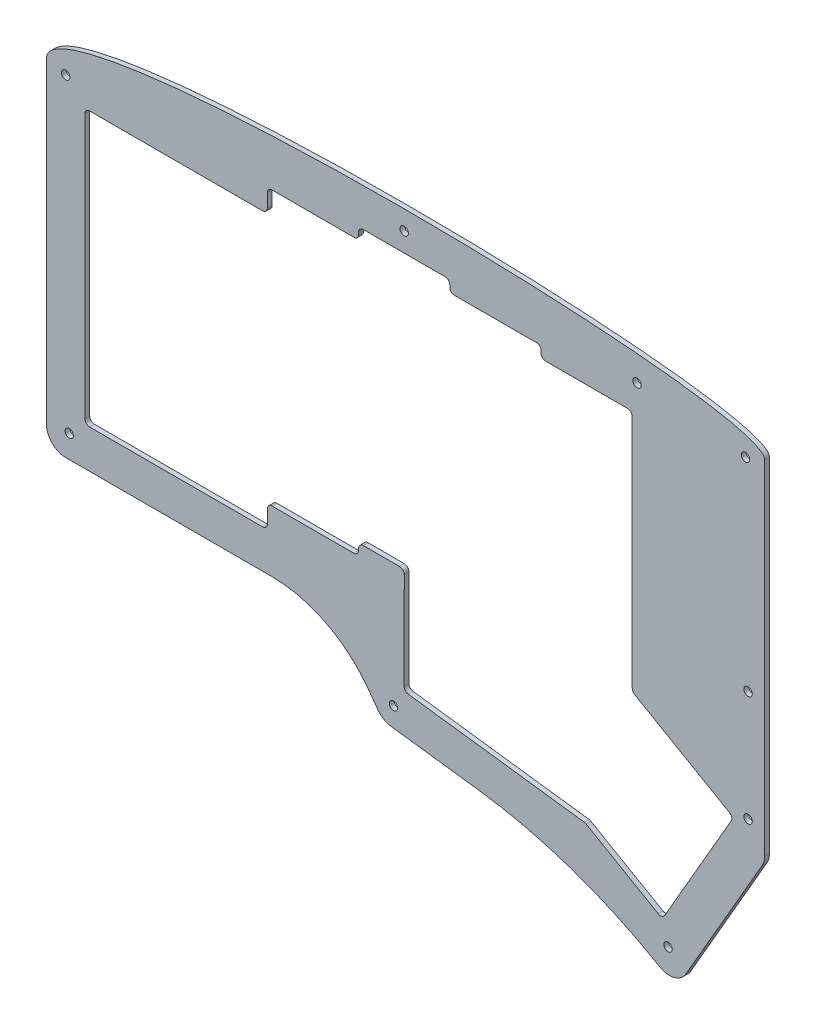
SolidWorks part; units mm, degrees
ref_plane "Front Plane" through (0, 0, 0) normal (0, 0, 1) x (1, 0, 0)
ref_plane "Top Plane" through (0, 0, 0) normal (0, 1, 0) x (1, 0, 0)
ref_plane "Right Plane" through (0, 0, 0) normal (1, 0, 0) x (0, 0, -1)
sketch "Model" plane through (0, 0, 0) normal (0, 0, 1) x (1, 0, 0)
  line L0 (-21.8431, 7.4481) -> (-8.6148, 30.3792)
  line L1 (-38.0636, 15.3297) -> (-23.771, 7.0696)
  line L2 (-75.3888, 20.2293) -> (-38.7189, 15.4592)
  line L3 (-86.2854, 34.8343) -> (-75.7419, 20.3766)
  line L4 (-29.1405, 92.9799) -> (-29.1405, 91.7303)
  line L5 (-8.8891, 91.2299) -> (-28.6402, 91.2299)
  line L6 (-8.3888, 90.7295) -> (-8.3888, 31.2555)
  line L7 (-86.6385, 34.9791) -> (-141.6396, 34.9791)
  line L8 (-142.1399, 90.7295) -> (-142.1399, 35.4795)
  line L9 (-104.6394, 91.2299) -> (-141.6396, 91.2299)
  line L10 (-104.139, 95.4793) -> (-104.139, 91.7303)
  line L11 (-85.6402, 95.9797) -> (-103.6387, 95.9797)
  line L12 (-85.1399, 97.7297) -> (-85.1399, 96.4801)
  line L13 (-67.6393, 98.2301) -> (-84.6395, 98.2301)
  line L14 (-67.1389, 96.4801) -> (-67.1389, 97.7297)
  line L15 (-48.6401, 95.9797) -> (-66.6385, 95.9797)
  line L16 (-48.1397, 93.9807) -> (-48.1397, 95.4793)
  line L17 (-29.6384, 93.4803) -> (-47.6393, 93.4803)
  line L18 (135.1563, 30.6526) -> (116.2359, 41.5721)
  line L19 (123.1828, 7.2669) -> (135.5373, 28.7222)
  line L20 (106.9623, 15.1485) -> (121.2549, 6.8884)
  line L21 (69.6371, 20.0481) -> (106.307, 15.278)
  line L22 (58.7405, 34.6531) -> (69.284, 20.1955)
  line L23 (115.8854, 92.7987) -> (115.8828, 42.2376)
  line L24 (58.3874, 34.7979) -> (3.3863, 34.7979)
  line L25 (2.886, 90.5483) -> (2.886, 35.2983)
  line L26 (40.3865, 91.0487) -> (3.3863, 91.0487)
  line L27 (40.8869, 95.2981) -> (40.8869, 91.5491)
  line L28 (59.3857, 95.7985) -> (41.3872, 95.7985)
  line L29 (59.886, 97.5485) -> (59.886, 96.2989)
  line L30 (77.3866, 98.0489) -> (60.3864, 98.0489)
  line L31 (77.887, 96.2989) -> (77.887, 97.5485)
  line L32 (96.3858, 95.7985) -> (78.3874, 95.7985)
  line L33 (96.8862, 93.7995) -> (96.8862, 95.2981)
  line L34 (115.3875, 93.2991) -> (97.3866, 93.2991)
  line L35 (20.1915, -96.2476) -> (6.9631, -73.3165)
  line L36 (36.4119, -88.366) -> (22.1193, -96.6261)
  line L37 (73.7371, -83.4663) -> (37.0672, -88.2365)
  line L38 (84.6337, -68.8614) -> (74.0902, -83.319)
  line L39 (27.4889, -10.7157) -> (27.4889, -11.9654)
  line L40 (7.2375, -12.4658) -> (26.9885, -12.4658)
  line L41 (6.7371, -12.9662) -> (6.7371, -72.4402)
  line L42 (84.9868, -68.7166) -> (139.9879, -68.7166)
  line L43 (140.4883, -12.9662) -> (140.4883, -68.2162)
  line L44 (102.9878, -12.4658) -> (139.9879, -12.4658)
  line L45 (102.4874, -8.2164) -> (102.4874, -11.9654)
  line L46 (83.9886, -7.716) -> (101.987, -7.716)
  line L47 (83.4882, -5.9659) -> (83.4882, -7.2156)
  line L48 (65.9876, -5.4656) -> (82.9878, -5.4656)
  line L49 (65.4872, -7.2156) -> (65.4872, -5.9659)
  line L50 (46.9884, -7.716) -> (64.9869, -7.716)
  line L51 (46.488, -9.715) -> (46.488, -8.2164)
  line L52 (27.9867, -10.2154) -> (45.9877, -10.2154)
  line L53 (-136.808, -73.043) -> (-117.8876, -62.1236)
  line L54 (-124.8344, -96.4288) -> (-137.189, -74.9734)
  line L55 (-108.614, -88.5472) -> (-122.9066, -96.8073)
  line L56 (-71.2888, -83.6475) -> (-107.9587, -88.4176)
  line L57 (-60.3922, -69.0425) -> (-70.9357, -83.5002)
  line L58 (-117.537, -10.8969) -> (-117.5345, -61.4581)
  line L59 (-60.0391, -68.8978) -> (-5.038, -68.8978)
  line L60 (-4.5376, -13.1474) -> (-4.5376, -68.3974)
  line L61 (-42.0381, -12.647) -> (-5.038, -12.647)
  line L62 (-42.5385, -8.3976) -> (-42.5385, -12.1466)
  line L63 (-61.0373, -7.8972) -> (-43.0389, -7.8972)
  line L64 (-61.5377, -6.1471) -> (-61.5377, -7.3968)
  line L65 (-79.0383, -5.6467) -> (-62.0381, -5.6467)
  line L66 (-79.5387, -7.3968) -> (-79.5387, -6.1471)
  line L67 (-98.0375, -7.8972) -> (-80.039, -7.8972)
  line L68 (-98.5378, -9.8962) -> (-98.5378, -8.3976)
  line L69 (-117.0392, -10.3965) -> (-99.0382, -10.3965)
  line L70 (138.9148, 92.1117) -> (138.9148, 33.3582)
  line L71 (138.1649, 32.9251) -> (119.446, 43.7282)
  line L72 (119.196, 44.1613) -> (119.196, 92.1092)
  line L73 (119.6959, 92.6092) -> (138.4148, 92.6117)
  line L74 (-140.5665, -11.584) -> (-140.5665, -70.3375)
  line L75 (-139.8166, -70.7706) -> (-121.0977, -59.9674)
  line L76 (-120.8476, -59.5344) -> (-120.8476, -11.5865)
  line L77 (-121.3476, -11.0865) -> (-140.0664, -11.084)
  line L78 (18.8966, 74.9256) -> (4.8966, 74.9256)
  line L79 (4.8966, 74.9256) -> (4.8966, 88.9256)
  line L80 (4.8966, 88.9256) -> (18.8966, 88.9256)
  line L81 (18.8966, 88.9256) -> (18.8966, 74.9256)
  line L82 (18.8966, 55.9256) -> (4.8966, 55.9256)
  line L83 (4.8966, 55.9256) -> (4.8966, 69.9256)
  line L84 (4.8966, 69.9256) -> (18.8966, 69.9256)
  line L85 (18.8966, 69.9256) -> (18.8966, 55.9256)
  line L86 (18.8966, 36.9256) -> (4.8966, 36.9256)
  line L87 (4.8966, 36.9256) -> (4.8966, 50.9256)
  line L88 (4.8966, 50.9256) -> (18.8966, 50.9256)
  line L89 (18.8966, 50.9256) -> (18.8966, 36.9256)
  line L90 (37.8948, 74.9262) -> (23.8948, 74.9262)
  line L91 (23.8948, 74.9262) -> (23.8948, 88.9262)
  line L92 (23.8948, 88.9262) -> (37.8948, 88.9262)
  line L93 (37.8948, 88.9262) -> (37.8948, 74.9262)
  line L94 (37.8948, 55.9262) -> (23.8948, 55.9262)
  line L95 (23.8948, 55.9262) -> (23.8948, 69.9262)
  line L96 (23.8948, 69.9262) -> (37.8948, 69.9262)
  line L97 (37.8948, 69.9262) -> (37.8948, 55.9262)
  line L98 (37.8948, 36.9262) -> (23.8948, 36.9262)
  line L99 (23.8948, 36.9262) -> (23.8948, 50.9262)
  line L100 (23.8948, 50.9262) -> (37.8948, 50.9262)
  line L101 (37.8948, 50.9262) -> (37.8948, 36.9262)
  line L102 (56.895, 79.671) -> (42.895, 79.671)
  line L103 (42.895, 79.671) -> (42.895, 93.671)
  line L104 (42.895, 93.671) -> (56.895, 93.671)
  line L105 (56.895, 93.671) -> (56.895, 79.671)
  line L106 (56.895, 60.6711) -> (42.895, 60.6711)
  line L107 (42.895, 60.6711) -> (42.895, 74.6711)
  line L108 (42.895, 74.6711) -> (56.895, 74.6711)
  line L109 (56.895, 74.6711) -> (56.895, 60.6711)
  line L110 (56.895, 41.6711) -> (42.895, 41.6711)
  line L111 (42.895, 41.6711) -> (42.895, 55.6711)
  line L112 (42.895, 55.6711) -> (56.895, 55.6711)
  line L113 (56.895, 55.6711) -> (56.895, 41.6711)
  line L114 (75.897, 82.0499) -> (61.897, 82.0499)
  line L115 (61.897, 82.0499) -> (61.897, 96.0499)
  line L116 (61.897, 96.0499) -> (75.897, 96.0499)
  line L117 (75.897, 96.0499) -> (75.897, 82.0499)
  line L118 (75.897, 63.0499) -> (61.897, 63.0499)
  line L119 (61.897, 63.0499) -> (61.897, 77.0499)
  line L120 (61.897, 77.0499) -> (75.897, 77.0499)
  line L121 (75.897, 77.0499) -> (75.897, 63.0499)
  line L122 (75.897, 44.0499) -> (61.897, 44.0499)
  line L123 (61.897, 44.0499) -> (61.897, 58.0499)
  line L124 (61.897, 58.0499) -> (75.897, 58.0499)
  line L125 (75.897, 58.0499) -> (75.897, 44.0499)
  line L126 (94.8982, 79.6753) -> (80.8982, 79.6753)
  line L127 (80.8982, 79.6753) -> (80.8982, 93.6753)
  line L128 (80.8982, 93.6753) -> (94.8982, 93.6753)
  line L129 (94.8982, 93.6753) -> (94.8982, 79.6753)
  line L130 (94.8982, 60.6753) -> (80.8982, 60.6753)
  line L131 (80.8982, 60.6753) -> (80.8982, 74.6753)
  line L132 (80.8982, 74.6753) -> (94.8982, 74.6753)
  line L133 (94.8982, 74.6753) -> (94.8982, 60.6753)
  line L134 (94.8982, 41.6753) -> (80.8982, 41.6753)
  line L135 (80.8982, 41.6753) -> (80.8982, 55.6753)
  line L136 (80.8982, 55.6753) -> (94.8982, 55.6753)
  line L137 (94.8982, 55.6753) -> (94.8982, 41.6753)
  line L138 (113.9, 77.2905) -> (99.9, 77.2905)
  line L139 (99.9, 77.2905) -> (99.9, 91.2905)
  line L140 (99.9, 91.2905) -> (113.9, 91.2905)
  line L141 (113.9, 91.2905) -> (113.9, 77.2905)
  line L142 (113.9, 58.2905) -> (99.9, 58.2905)
  line L143 (99.9, 58.2905) -> (99.9, 72.2905)
  line L144 (99.9, 72.2905) -> (113.9, 72.2905)
  line L145 (113.9, 72.2905) -> (113.9, 58.2905)
  line L146 (113.9, 39.2905) -> (99.9, 39.2905)
  line L147 (99.9, 39.2905) -> (99.9, 53.2905)
  line L148 (99.9, 53.2905) -> (113.9, 53.2905)
  line L149 (113.9, 53.2905) -> (113.9, 39.2905)
  line L150 (85.4166, 22.0174) -> (71.4166, 22.0174)
  line L151 (71.4166, 22.0174) -> (71.4166, 36.0174)
  line L152 (71.4166, 36.0174) -> (85.4166, 36.0174)
  line L153 (85.4166, 36.0174) -> (85.4166, 22.0174)
  line L154 (104.3289, 17.734) -> (90.806, 21.3575)
  line L155 (90.806, 21.3575) -> (94.4294, 34.8805)
  line L156 (94.4294, 34.8805) -> (107.9524, 31.257)
  line L157 (107.9524, 31.257) -> (104.3289, 17.734)
  line L158 (124.1994, 13.0049) -> (112.075, 20.0049)
  line L159 (112.075, 20.0049) -> (119.075, 32.1293)
  line L160 (119.075, 32.1293) -> (131.1994, 25.1293)
  line L161 (131.1994, 25.1293) -> (124.1994, 13.0049)
  line L162 (-20.5483, -28.7701) -> (-6.5483, -28.7701)
  line L163 (-6.5483, -28.7701) -> (-6.5483, -14.7701)
  line L164 (-6.5483, -14.7701) -> (-20.5483, -14.7701)
  line L165 (-20.5483, -14.7701) -> (-20.5483, -28.7701)
  line L166 (-20.5483, -47.7701) -> (-6.5483, -47.7701)
  line L167 (-6.5483, -47.7701) -> (-6.5483, -33.7701)
  line L168 (-6.5483, -33.7701) -> (-20.5483, -33.7701)
  line L169 (-20.5483, -33.7701) -> (-20.5483, -47.7701)
  line L170 (-20.5483, -66.7701) -> (-6.5483, -66.7701)
  line L171 (-6.5483, -66.7701) -> (-6.5483, -52.7701)
  line L172 (-6.5483, -52.7701) -> (-20.5483, -52.7701)
  line L173 (-20.5483, -52.7701) -> (-20.5483, -66.7701)
  line L174 (-39.5464, -28.7694) -> (-25.5464, -28.7694)
  line L175 (-25.5464, -28.7694) -> (-25.5464, -14.7694)
  line L176 (-25.5464, -14.7694) -> (-39.5464, -14.7694)
  line L177 (-39.5464, -14.7694) -> (-39.5464, -28.7694)
  line L178 (-39.5464, -47.7694) -> (-25.5464, -47.7694)
  line L179 (-25.5464, -47.7694) -> (-25.5464, -33.7694)
  line L180 (-25.5464, -33.7694) -> (-39.5464, -33.7694)
  line L181 (-39.5464, -33.7694) -> (-39.5464, -47.7694)
  line L182 (-39.5464, -66.7694) -> (-25.5464, -66.7694)
  line L183 (-25.5464, -66.7694) -> (-25.5464, -52.7694)
  line L184 (-25.5464, -52.7694) -> (-39.5464, -52.7694)
  line L185 (-39.5464, -52.7694) -> (-39.5464, -66.7694)
  line L186 (-58.5467, -24.0246) -> (-44.5467, -24.0246)
  line L187 (-44.5467, -24.0246) -> (-44.5467, -10.0246)
  line L188 (-44.5467, -10.0246) -> (-58.5467, -10.0246)
  line L189 (-58.5467, -10.0246) -> (-58.5467, -24.0246)
  line L190 (-58.5467, -43.0246) -> (-44.5467, -43.0246)
  line L191 (-44.5467, -43.0246) -> (-44.5467, -29.0246)
  line L192 (-44.5467, -29.0246) -> (-58.5467, -29.0246)
  line L193 (-58.5467, -29.0246) -> (-58.5467, -43.0246)
  line L194 (-58.5467, -62.0246) -> (-44.5467, -62.0246)
  line L195 (-44.5467, -62.0246) -> (-44.5467, -48.0246)
  line L196 (-44.5467, -48.0246) -> (-58.5467, -48.0246)
  line L197 (-58.5467, -48.0246) -> (-58.5467, -62.0246)
  line L198 (-77.5486, -21.6458) -> (-63.5486, -21.6458)
  line L199 (-63.5486, -21.6458) -> (-63.5486, -7.6458)
  line L200 (-63.5486, -7.6458) -> (-77.5486, -7.6458)
  line L201 (-77.5486, -7.6458) -> (-77.5486, -21.6458)
  line L202 (-77.5486, -40.6458) -> (-63.5486, -40.6458)
  line L203 (-63.5486, -40.6458) -> (-63.5486, -26.6458)
  line L204 (-63.5486, -26.6458) -> (-77.5486, -26.6458)
  line L205 (-77.5486, -26.6458) -> (-77.5486, -40.6458)
  line L206 (-77.5486, -59.6458) -> (-63.5486, -59.6458)
  line L207 (-63.5486, -59.6458) -> (-63.5486, -45.6458)
  line L208 (-63.5486, -45.6458) -> (-77.5486, -45.6458)
  line L209 (-77.5486, -45.6458) -> (-77.5486, -59.6458)
  line L210 (-96.5499, -24.0204) -> (-82.5499, -24.0204)
  line L211 (-82.5499, -24.0204) -> (-82.5499, -10.0204)
  line L212 (-82.5499, -10.0204) -> (-96.5499, -10.0204)
  line L213 (-96.5499, -10.0204) -> (-96.5499, -24.0204)
  line L214 (-96.5499, -43.0203) -> (-82.5499, -43.0203)
  line L215 (-82.5499, -43.0203) -> (-82.5499, -29.0203)
  line L216 (-82.5499, -29.0203) -> (-96.5499, -29.0203)
  line L217 (-96.5499, -29.0203) -> (-96.5499, -43.0203)
  line L218 (-96.5499, -62.0203) -> (-82.5499, -62.0203)
  line L219 (-82.5499, -62.0203) -> (-82.5499, -48.0203)
  line L220 (-82.5499, -48.0203) -> (-96.5499, -48.0203)
  line L221 (-96.5499, -48.0203) -> (-96.5499, -62.0203)
  line L222 (-115.5516, -26.4052) -> (-101.5516, -26.4052)
  line L223 (-101.5516, -26.4052) -> (-101.5516, -12.4052)
  line L224 (-101.5516, -12.4052) -> (-115.5516, -12.4052)
  line L225 (-115.5516, -12.4052) -> (-115.5516, -26.4052)
  line L226 (-115.5516, -45.4052) -> (-101.5516, -45.4052)
  line L227 (-101.5516, -45.4052) -> (-101.5516, -31.4052)
  line L228 (-101.5516, -31.4052) -> (-115.5516, -31.4052)
  line L229 (-115.5516, -31.4052) -> (-115.5516, -45.4052)
  line L230 (-115.5516, -64.4052) -> (-101.5516, -64.4052)
  line L231 (-101.5516, -64.4052) -> (-101.5516, -50.4052)
  line L232 (-101.5516, -50.4052) -> (-115.5516, -50.4052)
  line L233 (-115.5516, -50.4052) -> (-115.5516, -64.4052)
  line L234 (-87.0683, -81.6783) -> (-73.0683, -81.6783)
  line L235 (-73.0683, -81.6783) -> (-73.0683, -67.6783)
  line L236 (-73.0683, -67.6783) -> (-87.0683, -67.6783)
  line L237 (-87.0683, -67.6783) -> (-87.0683, -81.6783)
  line L238 (-105.9806, -85.9616) -> (-92.4576, -82.3382)
  line L239 (-92.4576, -82.3382) -> (-96.0811, -68.8152)
  line L240 (-96.0811, -68.8152) -> (-109.6041, -72.4387)
  line L241 (-109.6041, -72.4387) -> (-105.9806, -85.9616)
  line L242 (-125.851, -90.6908) -> (-113.7267, -83.6908)
  line L243 (-113.7267, -83.6908) -> (-120.7267, -71.5664)
  line L244 (-120.7267, -71.5664) -> (-132.851, -78.5664)
  line L245 (-132.851, -78.5664) -> (-125.851, -90.6908)
  spline S0 degree 3 poles (-8.6153, 30.3807) (-8.4626, 30.6458) (-8.3842, 30.9472) (-8.3882, 31.2532) knots 0 0 0 0 1 1 1 1
  spline S1 degree 3 poles (-21.8439, 7.4422) (-21.8429, 7.4437) (-21.8419, 7.4453) (-21.8408, 7.4468) knots 1 1 1 1 2 2 2 2
  spline S2 degree 3 poles (-23.769, 7.0673) (-23.1339, 6.6392) (-22.272, 6.8071) (-21.8439, 7.4422) knots 0 0 0 0 1 1 1 1
  spline S3 degree 3 poles (-38.063, 15.3284) (-38.2765, 15.3928) (-38.4957, 15.4362) (-38.7176, 15.4579) knots 0 0 0 0 1 1 1 1
  spline S4 degree 3 poles (-75.7416, 20.3746) (-75.6478, 20.2809) (-75.5206, 20.2283) (-75.3881, 20.2283) knots 0 0 0 0 1 1 1 1
  spline S5 degree 3 poles (-29.1383, 92.9782) (-29.1382, 93.2543) (-29.362, 93.4782) (-29.6381, 93.4783) knots 0 0 0 0 1 1 1 1
  spline S6 degree 3 poles (-29.1383, 91.7282) (-29.1383, 91.4521) (-28.9145, 91.2282) (-28.6384, 91.2281) (-28.6383, 91.2281) (-28.6382, 91.2281) (-28.6381, 91.2281) knots 0 0 0 0 1 1 1 2 2 2 2
  spline S7 degree 3 poles (-86.2846, 34.8318) (-86.3784, 34.9256) (-86.5056, 34.9783) (-86.6385, 34.9791) knots 0 0 0 0 1 1 1 1
  spline S8 degree 3 poles (-142.1382, 35.4782) (-142.1381, 35.2021) (-141.9142, 34.9783) (-141.6381, 34.9783) knots 0 0 0 0 1 1 1 1
  spline S9 degree 3 poles (-141.638, 91.2281) (-141.9142, 91.2282) (-142.1381, 91.0044) (-142.1382, 90.7282) knots 0 0 0 0 1 1 1 1
  spline S10 degree 3 poles (-104.6382, 91.2281) (-104.362, 91.228) (-104.1381, 91.4518) (-104.138, 91.728) (-104.138, 91.7281) (-104.138, 91.7281) (-104.138, 91.7282) knots 0 0 0 0 1 1 1 2 2 2 2
  spline S11 degree 3 poles (-103.6382, 95.9781) (-103.9142, 95.9781) (-104.138, 95.7543) (-104.138, 95.4783) knots 0 0 0 0 1 1 1 1
  spline S12 degree 3 poles (-85.6382, 95.9781) (-85.3621, 95.9781) (-85.1382, 96.2019) (-85.1381, 96.478) (-85.1381, 96.4781) (-85.1381, 96.4782) (-85.1381, 96.4783) knots 0 0 0 0 1 1 1 2 2 2 2
  spline S13 degree 3 poles (-84.6382, 98.2283) (-84.9144, 98.2283) (-85.1382, 98.0044) (-85.1381, 97.7282) knots 0 0 0 0 1 1 1 1
  spline S14 degree 3 poles (-67.1381, 97.7282) (-67.1381, 98.0043) (-67.3619, 98.2283) (-67.638, 98.2283) knots 0 0 0 0 2 2 2 2
  spline S15 degree 3 poles (-67.1381, 96.4783) (-67.1382, 96.2021) (-66.9144, 95.9782) (-66.6383, 95.9781) (-66.6382, 95.9781) (-66.6381, 95.9781) (-66.638, 95.9781) knots 0 0 0 0 1 1 1 2 2 2 2
  spline S16 degree 3 poles (-48.1382, 95.4783) (-48.1383, 95.7543) (-48.362, 95.9781) (-48.6381, 95.9781) knots 0 0 0 0 1 1 1 1
  spline S17 degree 3 poles (-48.1382, 93.9782) (-48.1381, 93.702) (-47.9142, 93.4782) (-47.6381, 93.4783) knots 0 0 0 0 1 1 1 1
  spline S18 degree 3 poles (-8.3882, 90.7282) (-8.3883, 91.0043) (-8.6121, 91.228) (-8.8881, 91.2281) knots 0 0 0 0 1 1 1 1
  spline S19 degree 3 poles (115.8851, 42.2368) (115.8929, 41.9725) (116.0232, 41.7268) (116.2377, 41.5721) knots 0 0 0 0 1 1 1 1
  spline S20 degree 3 poles (135.163, 30.647) (135.1614, 30.648) (135.1599, 30.6491) (135.1583, 30.6501) knots 1 1 1 1 2 2 2 2
  spline S21 degree 3 poles (135.5373, 28.7222) (135.9659, 29.3571) (135.7981, 30.2189) (135.163, 30.647) knots 0 0 0 0 1 1 1 1
  spline S22 degree 3 poles (123.182, 7.261) (123.183, 7.2625) (123.184, 7.2641) (123.1851, 7.2656) knots 1 1 1 1 2 2 2 2
  spline S23 degree 3 poles (121.2569, 6.8861) (121.892, 6.4581) (122.7539, 6.6259) (123.182, 7.261) knots 0 0 0 0 1 1 1 1
  spline S24 degree 3 poles (106.9629, 15.1472) (106.7494, 15.2117) (106.5302, 15.255) (106.3083, 15.2768) knots 0 0 0 0 1 1 1 1
  spline S25 degree 3 poles (69.2843, 20.1934) (69.3781, 20.0997) (69.5053, 20.0471) (69.6378, 20.0471) knots 0 0 0 0 1 1 1 1
  spline S26 degree 3 poles (115.8876, 92.797) (115.8877, 93.0731) (115.6639, 93.297) (115.3878, 93.2971) knots 0 0 0 0 1 1 1 1
  spline S27 degree 3 poles (58.7413, 34.6506) (58.6475, 34.7444) (58.5203, 34.7971) (58.3874, 34.7979) knots 0 0 0 0 1 1 1 1
  spline S28 degree 3 poles (2.8877, 35.297) (2.8878, 35.0209) (3.1117, 34.7971) (3.3878, 34.7971) knots 0 0 0 0 1 1 1 1
  spline S29 degree 3 poles (3.3879, 91.0469) (3.1117, 91.047) (2.8878, 90.8232) (2.8877, 90.547) knots 0 0 0 0 1 1 1 1
  spline S30 degree 3 poles (40.3877, 91.0469) (40.6639, 91.0468) (40.8878, 91.2706) (40.8879, 91.5468) (40.8879, 91.5469) (40.8879, 91.5469) (40.8879, 91.547) knots 0 0 0 0 1 1 1 2 2 2 2
  spline S31 degree 3 poles (41.3877, 95.797) (41.1117, 95.7969) (40.8879, 95.5731) (40.8879, 95.2971) knots 0 0 0 0 1 1 1 1
  spline S32 degree 3 poles (59.3877, 95.797) (59.6638, 95.7969) (59.8877, 96.0207) (59.8878, 96.2968) (59.8878, 96.2969) (59.8878, 96.297) (59.8878, 96.2971) knots 0 0 0 0 1 1 1 2 2 2 2
  spline S33 degree 3 poles (60.3877, 98.0471) (60.1115, 98.0471) (59.8877, 97.8232) (59.8878, 97.547) knots 0 0 0 0 1 1 1 1
  spline S34 degree 3 poles (77.8878, 97.547) (77.8878, 97.8232) (77.664, 98.0471) (77.3879, 98.0471) knots 0 0 0 0 2 2 2 2
  spline S35 degree 3 poles (77.8878, 96.2971) (77.8877, 96.0209) (78.1115, 95.797) (78.3876, 95.797) (78.3877, 95.797) (78.3878, 95.797) (78.3879, 95.797) knots 0 0 0 0 1 1 1 2 2 2 2
  spline S36 degree 3 poles (96.8877, 95.2971) (96.8876, 95.5731) (96.6639, 95.7969) (96.3878, 95.797) knots 0 0 0 0 1 1 1 1
  spline S37 degree 3 poles (96.8877, 93.797) (96.8878, 93.5208) (97.1117, 93.297) (97.3878, 93.2971) knots 0 0 0 0 1 1 1 1
  spline S38 degree 3 poles (6.9637, -73.315) (6.8109, -73.0499) (6.7325, -72.7484) (6.7366, -72.4425) knots 0 0 0 0 1 1 1 1
  spline S39 degree 3 poles (20.1923, -96.2535) (20.1912, -96.252) (20.1902, -96.2504) (20.1892, -96.2489) knots 1 1 1 1 2 2 2 2
  spline S40 degree 3 poles (22.1173, -96.6284) (21.4822, -97.0564) (20.6203, -96.8886) (20.1923, -96.2535) knots 0 0 0 0 1 1 1 1
  spline S41 degree 3 poles (36.4114, -88.3673) (36.6248, -88.3028) (36.844, -88.2594) (37.0659, -88.2377) knots 0 0 0 0 1 1 1 1
  spline S42 degree 3 poles (74.0899, -83.3211) (73.9962, -83.4148) (73.869, -83.4674) (73.7364, -83.4674) knots 0 0 0 0 1 1 1 1
  spline S43 degree 3 poles (27.4866, -10.7175) (27.4865, -10.4414) (27.7103, -10.2175) (27.9865, -10.2174) knots 0 0 0 0 1 1 1 1
  spline S44 degree 3 poles (27.4866, -11.9674) (27.4866, -12.2436) (27.2628, -12.4675) (26.9867, -12.4676) (26.9866, -12.4676) (26.9865, -12.4676) (26.9865, -12.4676) knots 0 0 0 0 1 1 1 2 2 2 2
  spline S45 degree 3 poles (84.633, -68.8639) (84.7267, -68.7701) (84.8539, -68.7174) (84.9868, -68.7166) knots 0 0 0 0 1 1 1 1
  spline S46 degree 3 poles (140.4865, -68.2175) (140.4864, -68.4936) (140.2625, -68.7174) (139.9864, -68.7173) knots 0 0 0 0 1 1 1 1
  spline S47 degree 3 poles (139.9864, -12.4676) (140.2625, -12.4675) (140.4864, -12.6913) (140.4865, -12.9674) knots 0 0 0 0 1 1 1 1
  spline S48 degree 3 poles (102.9865, -12.4676) (102.7103, -12.4676) (102.4864, -12.2438) (102.4864, -11.9677) (102.4864, -11.9676) (102.4864, -11.9675) (102.4864, -11.9674) knots 0 0 0 0 1 1 1 2 2 2 2
  spline S49 degree 3 poles (101.9865, -7.7175) (102.2625, -7.7176) (102.4863, -7.9413) (102.4864, -8.2174) knots 0 0 0 0 1 1 1 1
  spline S50 degree 3 poles (83.9865, -7.7175) (83.7104, -7.7176) (83.4865, -7.4938) (83.4864, -7.2176) (83.4864, -7.2176) (83.4864, -7.2175) (83.4864, -7.2174) knots 0 0 0 0 1 1 1 2 2 2 2
  spline S51 degree 3 poles (82.9865, -5.4673) (83.2627, -5.4674) (83.4865, -5.6913) (83.4864, -5.9675) knots 0 0 0 0 1 1 1 1
  spline S52 degree 3 poles (65.4865, -5.9675) (65.4864, -5.6913) (65.7102, -5.4674) (65.9863, -5.4673) knots 0 0 0 0 2 2 2 2
  spline S53 degree 3 poles (65.4865, -7.2174) (65.4865, -7.4935) (65.2627, -7.7174) (64.9866, -7.7175) (64.9865, -7.7175) (64.9864, -7.7175) (64.9863, -7.7175) knots 0 0 0 0 1 1 1 2 2 2 2
  spline S54 degree 3 poles (46.4865, -8.2174) (46.4866, -7.9413) (46.7103, -7.7176) (46.9864, -7.7175) knots 0 0 0 0 1 1 1 1
  spline S55 degree 3 poles (46.4865, -9.7175) (46.4865, -9.9937) (46.2625, -10.2175) (45.9864, -10.2174) knots 0 0 0 0 1 1 1 1
  spline S56 degree 3 poles (6.7366, -12.9674) (6.7366, -12.6914) (6.9604, -12.4676) (7.2365, -12.4676) knots 0 0 0 0 1 1 1 1
  spline S57 degree 3 poles (-117.5368, -61.4589) (-117.5446, -61.7232) (-117.6748, -61.9689) (-117.8893, -62.1236) knots 0 0 0 0 1 1 1 1
  spline S58 degree 3 poles (-136.8146, -73.0487) (-136.8131, -73.0476) (-136.8116, -73.0466) (-136.81, -73.0456) knots 1 1 1 1 2 2 2 2
  spline S59 degree 3 poles (-137.189, -74.9734) (-137.6176, -74.3386) (-137.4497, -73.4767) (-136.8146, -73.0487) knots 0 0 0 0 1 1 1 1
  spline S60 degree 3 poles (-124.8336, -96.4347) (-124.8347, -96.4331) (-124.8357, -96.4316) (-124.8367, -96.4301) knots 1 1 1 1 2 2 2 2
  spline S61 degree 3 poles (-122.9086, -96.8095) (-123.5437, -97.2376) (-124.4056, -97.0698) (-124.8336, -96.4347) knots 0 0 0 0 1 1 1 1
  spline S62 degree 3 poles (-108.6145, -88.5485) (-108.4011, -88.484) (-108.1819, -88.4406) (-107.96, -88.4189) knots 0 0 0 0 1 1 1 1
  spline S63 degree 3 poles (-70.936, -83.5022) (-71.0297, -83.596) (-71.1569, -83.6486) (-71.2895, -83.6485) knots 0 0 0 0 1 1 1 1
  spline S64 degree 3 poles (-117.5393, -10.8987) (-117.5394, -10.6226) (-117.3156, -10.3987) (-117.0394, -10.3986) knots 0 0 0 0 1 1 1 1
  spline S65 degree 3 poles (-60.3929, -69.0451) (-60.2992, -68.9513) (-60.172, -68.8986) (-60.0391, -68.8978) knots 0 0 0 0 1 1 1 1
  spline S66 degree 3 poles (-4.5394, -68.3987) (-4.5395, -68.6748) (-4.7634, -68.8986) (-5.0395, -68.8985) knots 0 0 0 0 1 1 1 1
  spline S67 degree 3 poles (-5.0395, -12.6488) (-4.7634, -12.6487) (-4.5395, -12.8725) (-4.5394, -13.1486) knots 0 0 0 0 1 1 1 1
  spline S68 degree 3 poles (-42.0394, -12.6488) (-42.3156, -12.6488) (-42.5395, -12.425) (-42.5395, -12.1489) (-42.5395, -12.1488) (-42.5395, -12.1487) (-42.5395, -12.1486) knots 0 0 0 0 1 1 1 2 2 2 2
  spline S69 degree 3 poles (-43.0394, -7.8987) (-42.7634, -7.8988) (-42.5396, -8.1225) (-42.5395, -8.3986) knots 0 0 0 0 1 1 1 1
  spline S70 degree 3 poles (-61.0394, -7.8987) (-61.3155, -7.8988) (-61.5394, -7.675) (-61.5395, -7.3988) (-61.5395, -7.3988) (-61.5395, -7.3987) (-61.5395, -7.3986) knots 0 0 0 0 1 1 1 2 2 2 2
  spline S71 degree 3 poles (-62.0394, -5.6485) (-61.7632, -5.6486) (-61.5394, -5.8725) (-61.5395, -6.1486) knots 0 0 0 0 1 1 1 1
  spline S72 degree 3 poles (-79.5394, -6.1486) (-79.5395, -5.8725) (-79.3157, -5.6486) (-79.0396, -5.6485) knots 0 0 0 0 2 2 2 2
  spline S73 degree 3 poles (-79.5394, -7.3986) (-79.5394, -7.6747) (-79.7632, -7.8986) (-80.0393, -7.8987) (-80.0394, -7.8987) (-80.0395, -7.8987) (-80.0396, -7.8987) knots 0 0 0 0 1 1 1 2 2 2 2
  spline S74 degree 3 poles (-98.5394, -8.3986) (-98.5393, -8.1225) (-98.3156, -7.8988) (-98.0395, -7.8987) knots 0 0 0 0 1 1 1 1
  spline S75 degree 3 poles (-98.5394, -9.8987) (-98.5394, -10.1748) (-98.7634, -10.3986) (-99.0395, -10.3986) knots 0 0 0 0 1 1 1 1
  spline S76 degree 3 poles (-123.6381, 52.6314) (-124.2456, 52.6314) (-124.7381, 53.1239) (-124.7381, 53.7314) (-124.7381, 54.3389) (-124.2456, 54.8314) (-123.6381, 54.8314) knots 2 2 2 2 3 3 3 4 4 4 4
  spline S77 degree 3 poles (-123.6381, 54.8314) (-123.0306, 54.8314) (-122.5381, 54.3389) (-122.5381, 53.7314) (-122.5381, 53.1239) (-123.0306, 52.6314) (-123.6381, 52.6314) knots 0 0 0 0 1 1 1 2 2 2 2
  spline S78 degree 3 poles (-123.6381, 71.3814) (-124.2456, 71.3814) (-124.7381, 71.8739) (-124.7381, 72.4814) (-124.7381, 73.0889) (-124.2456, 73.5814) (-123.6381, 73.5814) knots 2 2 2 2 3 3 3 4 4 4 4
  spline S79 degree 3 poles (-123.6381, 73.5814) (-123.0306, 73.5814) (-122.5381, 73.0889) (-122.5381, 72.4814) (-122.5381, 71.8739) (-123.0306, 71.3814) (-123.6381, 71.3814) knots 0 0 0 0 1 1 1 2 2 2 2
  spline S80 degree 3 poles (-47.6381, 75.1312) (-48.2456, 75.1312) (-48.7381, 75.6237) (-48.7381, 76.2312) (-48.7381, 76.8387) (-48.2456, 77.3312) (-47.6381, 77.3312) knots 2 2 2 2 3 3 3 4 4 4 4
  spline S81 degree 3 poles (-47.6381, 77.3312) (-47.0306, 77.3312) (-46.5381, 76.8387) (-46.5381, 76.2312) (-46.5381, 75.6237) (-47.0306, 75.1312) (-47.6381, 75.1312) knots 0 0 0 0 1 1 1 2 2 2 2
  spline S82 degree 3 poles (-80.388, 35.3813) (-80.9956, 35.3813) (-81.488, 35.8738) (-81.488, 36.4813) (-81.488, 37.0888) (-80.9956, 37.5813) (-80.388, 37.5813) knots 2 2 2 2 3 3 3 4 4 4 4
  spline S83 degree 3 poles (-80.388, 37.5813) (-79.7805, 37.5813) (-79.288, 37.0888) (-79.288, 36.4813) (-79.288, 35.8738) (-79.7805, 35.3813) (-80.388, 35.3813) knots 0 0 0 0 1 1 1 2 2 2 2
  spline S84 degree 3 poles (-33.8881, 27.6312) (-34.4956, 27.6312) (-34.9881, 28.1237) (-34.9881, 28.7312) (-34.9881, 29.3388) (-34.4956, 29.8312) (-33.8881, 29.8312) knots 2 2 2 2 3 3 3 4 4 4 4
  spline S85 degree 3 poles (-33.8881, 29.8312) (-33.2805, 29.8312) (-32.7881, 29.3388) (-32.7881, 28.7312) (-32.7881, 28.1237) (-33.2805, 27.6312) (-33.8881, 27.6312) knots 0 0 0 0 1 1 1 2 2 2 2
  spline S86 degree 3 poles (21.3878, 52.4502) (20.7803, 52.4502) (20.2878, 52.9427) (20.2878, 53.5502) (20.2878, 54.1578) (20.7803, 54.6502) (21.3878, 54.6502) knots 2 2 2 2 3 3 3 4 4 4 4
  spline S87 degree 3 poles (21.3878, 54.6502) (21.9953, 54.6502) (22.4878, 54.1578) (22.4878, 53.5502) (22.4878, 52.9427) (21.9953, 52.4502) (21.3878, 52.4502) knots 0 0 0 0 1 1 1 2 2 2 2
  spline S88 degree 3 poles (97.3878, 74.95) (96.7803, 74.95) (96.2878, 75.4425) (96.2878, 76.05) (96.2878, 76.6575) (96.7803, 77.15) (97.3878, 77.15) knots 2 2 2 2 3 3 3 4 4 4 4
  spline S89 degree 3 poles (97.3878, 77.15) (97.9953, 77.15) (98.4878, 76.6575) (98.4878, 76.05) (98.4878, 75.4425) (97.9953, 74.95) (97.3878, 74.95) knots 0 0 0 0 1 1 1 2 2 2 2
  spline S90 degree 3 poles (64.6379, 35.2001) (64.0303, 35.2001) (63.5379, 35.6926) (63.5379, 36.3001) (63.5379, 36.9076) (64.0303, 37.4001) (64.6379, 37.4001) knots 2 2 2 2 3 3 3 4 4 4 4
  spline S91 degree 3 poles (64.6379, 37.4001) (65.2454, 37.4001) (65.7379, 36.9076) (65.7379, 36.3001) (65.7379, 35.6926) (65.2454, 35.2001) (64.6379, 35.2001) knots 0 0 0 0 1 1 1 2 2 2 2
  spline S92 degree 3 poles (111.1378, 27.4501) (110.5303, 27.4501) (110.0378, 27.9425) (110.0378, 28.5501) (110.0378, 29.1576) (110.5303, 29.65) (111.1378, 29.65) knots 2 2 2 2 3 3 3 4 4 4 4
  spline S93 degree 3 poles (111.1378, 29.65) (111.7454, 29.65) (112.2378, 29.1576) (112.2378, 28.5501) (112.2378, 27.9425) (111.7454, 27.4501) (111.1378, 27.4501) knots 0 0 0 0 1 1 1 2 2 2 2
  spline S94 degree 3 poles (121.9864, -51.0642) (122.5939, -51.0642) (123.0864, -50.5718) (123.0864, -49.9642) (123.0864, -49.3567) (122.5939, -48.8642) (121.9864, -48.8642) knots 2 2 2 2 3 3 3 4 4 4 4
  spline S95 degree 3 poles (121.9864, -48.8642) (121.3789, -48.8642) (120.8864, -49.3567) (120.8864, -49.9642) (120.8864, -50.5718) (121.3789, -51.0642) (121.9864, -51.0642) knots 0 0 0 0 1 1 1 2 2 2 2
  spline S96 degree 3 poles (121.9864, -32.3142) (122.5939, -32.3142) (123.0864, -31.8218) (123.0864, -31.2142) (123.0864, -30.6067) (122.5939, -30.1142) (121.9864, -30.1142) knots 2 2 2 2 3 3 3 4 4 4 4
  spline S97 degree 3 poles (121.9864, -30.1142) (121.3789, -30.1142) (120.8864, -30.6067) (120.8864, -31.2142) (120.8864, -31.8218) (121.3789, -32.3142) (121.9864, -32.3142) knots 0 0 0 0 1 1 1 2 2 2 2
  spline S98 degree 3 poles (45.9864, -28.5644) (46.5939, -28.5644) (47.0864, -28.072) (47.0864, -27.4644) (47.0864, -26.8569) (46.5939, -26.3644) (45.9864, -26.3644) knots 2 2 2 2 3 3 3 4 4 4 4
  spline S99 degree 3 poles (45.9864, -26.3644) (45.3789, -26.3644) (44.8864, -26.8569) (44.8864, -27.4644) (44.8864, -28.072) (45.3789, -28.5644) (45.9864, -28.5644) knots 0 0 0 0 1 1 1 2 2 2 2
  spline S100 degree 3 poles (78.7364, -68.3144) (79.3439, -68.3144) (79.8364, -67.8219) (79.8364, -67.2144) (79.8364, -66.6069) (79.3439, -66.1144) (78.7364, -66.1144) knots 2 2 2 2 3 3 3 4 4 4 4
  spline S101 degree 3 poles (78.7364, -66.1144) (78.1288, -66.1144) (77.6364, -66.6069) (77.6364, -67.2144) (77.6364, -67.8219) (78.1288, -68.3144) (78.7364, -68.3144) knots 0 0 0 0 1 1 1 2 2 2 2
  spline S102 degree 3 poles (32.2364, -76.0644) (32.8439, -76.0644) (33.3364, -75.5719) (33.3364, -74.9644) (33.3364, -74.3569) (32.8439, -73.8644) (32.2364, -73.8644) knots 2 2 2 2 3 3 3 4 4 4 4
  spline S103 degree 3 poles (32.2364, -73.8644) (31.6289, -73.8644) (31.1364, -74.3569) (31.1364, -74.9644) (31.1364, -75.5719) (31.6289, -76.0644) (32.2364, -76.0644) knots 0 0 0 0 1 1 1 2 2 2 2
  spline S104 degree 3 poles (-23.0395, -51.2454) (-22.432, -51.2454) (-21.9395, -50.7529) (-21.9395, -50.1454) (-21.9395, -49.5379) (-22.432, -49.0454) (-23.0395, -49.0454) knots 2 2 2 2 3 3 3 4 4 4 4
  spline S105 degree 3 poles (-23.0395, -49.0454) (-23.647, -49.0454) (-24.1395, -49.5379) (-24.1395, -50.1454) (-24.1395, -50.7529) (-23.647, -51.2454) (-23.0395, -51.2454) knots 0 0 0 0 1 1 1 2 2 2 2
  spline S106 degree 3 poles (-99.0395, -28.7456) (-98.432, -28.7456) (-97.9395, -28.2531) (-97.9395, -27.6456) (-97.9395, -27.0381) (-98.432, -26.5456) (-99.0395, -26.5456) knots 2 2 2 2 3 3 3 4 4 4 4
  spline S107 degree 3 poles (-99.0395, -26.5456) (-99.647, -26.5456) (-100.1395, -27.0381) (-100.1395, -27.6456) (-100.1395, -28.2531) (-99.647, -28.7456) (-99.0395, -28.7456) knots 0 0 0 0 1 1 1 2 2 2 2
  spline S108 degree 3 poles (-66.2895, -68.4956) (-65.682, -68.4956) (-65.1895, -68.0031) (-65.1895, -67.3956) (-65.1895, -66.7881) (-65.682, -66.2956) (-66.2895, -66.2956) knots 2 2 2 2 3 3 3 4 4 4 4
  spline S109 degree 3 poles (-66.2895, -66.2956) (-66.8971, -66.2956) (-67.3895, -66.7881) (-67.3895, -67.3956) (-67.3895, -68.0031) (-66.8971, -68.4956) (-66.2895, -68.4956) knots 0 0 0 0 1 1 1 2 2 2 2
  spline S110 degree 3 poles (-112.7895, -76.2456) (-112.182, -76.2456) (-111.6895, -75.7531) (-111.6895, -75.1456) (-111.6895, -74.5381) (-112.182, -74.0456) (-112.7895, -74.0456) knots 2 2 2 2 3 3 3 4 4 4 4
  spline S111 degree 3 poles (-112.7895, -74.0456) (-113.397, -74.0456) (-113.8895, -74.5381) (-113.8895, -75.1456) (-113.8895, -75.7531) (-113.397, -76.2456) (-112.7895, -76.2456) knots 0 0 0 0 1 1 1 2 2 2 2
  spline S112 degree 3 poles (138.9148, 33.3582) (138.9148, 32.9733) (138.4982, 32.7327) (138.1649, 32.9251) knots 1 1 1 1 2 2 2 2
  spline S113 degree 3 poles (119.446, 43.7282) (119.2913, 43.8175) (119.196, 43.9826) (119.196, 44.1613) knots 3 3 3 3 4 4 4 4
  spline S114 degree 3 poles (119.196, 92.1092) (119.196, 92.3853) (119.4198, 92.6092) (119.6959, 92.6092) knots 5 5 5 5 6 6 6 6
  spline S115 degree 3 poles (138.4148, 92.6117) (138.6909, 92.6117) (138.9148, 92.3879) (138.9148, 92.1117) knots 7 7 7 7 8 8 8 8
  spline S116 degree 3 poles (-140.5665, -70.3375) (-140.5665, -70.7224) (-140.1499, -70.9629) (-139.8166, -70.7706) knots 1 1 1 1 2 2 2 2
  spline S117 degree 3 poles (-121.0977, -59.9674) (-120.943, -59.8781) (-120.8476, -59.7131) (-120.8476, -59.5344) knots 3 3 3 3 4 4 4 4
  spline S118 degree 3 poles (-120.8476, -11.5865) (-120.8476, -11.3103) (-121.0715, -11.0865) (-121.3476, -11.0865) knots 5 5 5 5 6 6 6 6
  spline S119 degree 3 poles (-140.0664, -11.084) (-140.3426, -11.0839) (-140.5665, -11.3078) (-140.5665, -11.584) knots 7 7 7 7 8 8 8 8
  spline S120 degree 3 poles (120.7443, 45.1272) (120.7443, 45.7347) (121.2368, 46.2272) (121.8443, 46.2272) (122.4518, 46.2272) (122.9443, 45.7347) (122.9443, 45.1272) knots 2 2 2 2 3 3 3 4 4 4 4
  spline S121 degree 3 poles (122.9443, 45.1272) (122.9443, 44.5197) (122.4518, 44.0272) (121.8443, 44.0272) (121.2368, 44.0272) (120.7443, 44.5197) (120.7443, 45.1272) knots 0 0 0 0 1 1 1 2 2 2 2
  spline S122 degree 3 poles (135.1763, 36.6063) (135.1763, 37.2138) (135.6688, 37.7063) (136.2763, 37.7063) (136.8838, 37.7063) (137.3763, 37.2138) (137.3763, 36.6063) knots 2 2 2 2 3 3 3 4 4 4 4
  spline S123 degree 3 poles (137.3763, 36.6063) (137.3763, 35.9988) (136.8838, 35.5063) (136.2763, 35.5063) (135.6688, 35.5063) (135.1763, 35.9988) (135.1763, 36.6063) knots 0 0 0 0 1 1 1 2 2 2 2
  spline S124 degree 3 poles (20.2878, 72.3002) (20.2878, 72.9078) (20.7803, 73.4002) (21.3878, 73.4002) (21.9953, 73.4002) (22.4878, 72.9078) (22.4878, 72.3002) knots 2 2 2 2 3 3 3 4 4 4 4
  spline S125 degree 3 poles (22.4878, 72.3002) (22.4878, 71.6927) (21.9953, 71.2002) (21.3878, 71.2002) (20.7803, 71.2002) (20.2878, 71.6927) (20.2878, 72.3002) knots 0 0 0 0 1 1 1 2 2 2 2
  spline S126 degree 3 poles (-122.3959, -58.5684) (-122.3959, -57.9609) (-122.8884, -57.4684) (-123.4959, -57.4684) (-124.1035, -57.4684) (-124.5959, -57.9609) (-124.5959, -58.5684) knots 2 2 2 2 3 3 3 4 4 4 4
  spline S127 degree 3 poles (-124.5959, -58.5684) (-124.5959, -59.1759) (-124.1035, -59.6684) (-123.4959, -59.6684) (-122.8884, -59.6684) (-122.3959, -59.1759) (-122.3959, -58.5684) knots 0 0 0 0 1 1 1 2 2 2 2
  spline S128 degree 3 poles (-136.8279, -67.0894) (-136.8279, -66.4818) (-137.3204, -65.9894) (-137.9279, -65.9894) (-138.5355, -65.9894) (-139.0279, -66.4818) (-139.0279, -67.0894) knots 2 2 2 2 3 3 3 4 4 4 4
  spline S129 degree 3 poles (-139.0279, -67.0894) (-139.0279, -67.6969) (-138.5355, -68.1894) (-137.9279, -68.1894) (-137.3204, -68.1894) (-136.8279, -67.6969) (-136.8279, -67.0894) knots 0 0 0 0 1 1 1 2 2 2 2
  spline S130 degree 3 poles (-21.9395, -31.3954) (-21.9395, -30.7879) (-22.432, -30.2954) (-23.0395, -30.2954) (-23.647, -30.2954) (-24.1395, -30.7879) (-24.1395, -31.3954) knots 2 2 2 2 3 3 3 4 4 4 4
  spline S131 degree 3 poles (-24.1395, -31.3954) (-24.1395, -32.0029) (-23.647, -32.4954) (-23.0395, -32.4954) (-22.432, -32.4954) (-21.9395, -32.0029) (-21.9395, -31.3954) knots 0 0 0 0 1 1 1 2 2 2 2
sketch "Sketch2" plane through (0, 0, 0) normal (0, 0, 1) x (1, 0, 0)
  line L0 (18.8966, 74.9256) -> (4.8966, 74.9256) construction
  line L1 (18.8966, 88.9256) -> (18.8966, 74.9256) construction
  line L2 (4.8966, 88.9256) -> (18.8966, 88.9256) construction
  line L3 (4.8966, 74.9256) -> (4.8966, 88.9256) construction
  line L4 (18.8966, 74.9256) -> (4.8966, 74.9256) construction
  line L5 (18.8966, 88.9256) -> (18.8966, 74.9256) construction
  line L6 (4.8966, 88.9256) -> (18.8966, 88.9256) construction
  line L7 (4.8966, 74.9256) -> (4.8966, 88.9256) construction
  line L8 (115.8854, 92.7987) -> (115.8828, 42.2376) construction
  line L9 (135.1563, 30.6526) -> (116.2359, 41.5721) construction
  line L10 (123.1828, 7.2669) -> (135.5373, 28.7222) construction
  line L11 (106.9623, 15.1485) -> (121.2549, 6.8884) construction
  line L12 (69.6371, 20.0481) -> (106.307, 15.278) construction
  line L13 (58.7405, 34.6531) -> (69.284, 20.1955) construction
  line L14 (85.4166, 36.0174) -> (85.4166, 22.0174) construction
  line L15 (85.4166, 22.0174) -> (71.4166, 22.0174) construction
  line L16 (71.4166, 22.0174) -> (71.4166, 36.0174) construction
  line L17 (71.4166, 36.0174) -> (85.4166, 36.0174) construction
  line L18 (107.9524, 31.257) -> (104.3289, 17.734) construction
  line L19 (104.3289, 17.734) -> (90.806, 21.3575) construction
  line L20 (90.806, 21.3575) -> (94.4294, 34.8805) construction
  line L21 (94.4294, 34.8805) -> (107.9524, 31.257) construction
  line L22 (112.075, 20.0049) -> (119.075, 32.1293) construction
  line L23 (119.075, 32.1293) -> (131.1994, 25.1293) construction
  line L24 (131.1994, 25.1293) -> (124.1994, 13.0049) construction
  line L25 (124.1994, 13.0049) -> (112.075, 20.0049) construction
  line L26 (99.9, 39.2905) -> (99.9, 53.2905) construction
  line L27 (99.9, 53.2905) -> (113.9, 53.2905) construction
  line L28 (113.9, 53.2905) -> (113.9, 39.2905) construction
  line L29 (113.9, 39.2905) -> (99.9, 39.2905) construction
  line L30 (80.8982, 41.6753) -> (80.8982, 55.6753) construction
  line L31 (80.8982, 55.6753) -> (94.8982, 55.6753) construction
  line L32 (94.8982, 55.6753) -> (94.8982, 41.6753) construction
  line L33 (94.8982, 41.6753) -> (80.8982, 41.6753) construction
  line L34 (58.3874, 34.7979) -> (3.3863, 34.7979) construction
  line L35 (61.897, 44.0499) -> (61.897, 58.0499) construction
  line L36 (61.897, 58.0499) -> (75.897, 58.0499) construction
  line L37 (75.897, 58.0499) -> (75.897, 44.0499) construction
  line L38 (75.897, 44.0499) -> (61.897, 44.0499) construction
  line L39 (42.895, 41.6711) -> (42.895, 55.6711) construction
  line L40 (42.895, 55.6711) -> (56.895, 55.6711) construction
  line L41 (56.895, 55.6711) -> (56.895, 41.6711) construction
  line L42 (56.895, 41.6711) -> (42.895, 41.6711) construction
  line L43 (23.8948, 36.9262) -> (23.8948, 50.9262) construction
  line L44 (23.8948, 50.9262) -> (37.8948, 50.9262) construction
  line L45 (37.8948, 50.9262) -> (37.8948, 36.9262) construction
  line L46 (37.8948, 36.9262) -> (23.8948, 36.9262) construction
  line L47 (18.8966, 50.9256) -> (18.8966, 36.9256) construction
  line L48 (18.8966, 36.9256) -> (4.8966, 36.9256) construction
  line L49 (4.8966, 36.9256) -> (4.8966, 50.9256) construction
  line L50 (4.8966, 50.9256) -> (18.8966, 50.9256) construction
  line L51 (99.9, 58.2905) -> (99.9, 72.2905) construction
  line L52 (99.9, 72.2905) -> (113.9, 72.2905) construction
  line L53 (113.9, 72.2905) -> (113.9, 58.2905) construction
  line L54 (113.9, 58.2905) -> (99.9, 58.2905) construction
  line L55 (94.8982, 74.6753) -> (94.8982, 60.6753) construction
  line L56 (94.8982, 60.6753) -> (80.8982, 60.6753) construction
  line L57 (80.8982, 60.6753) -> (80.8982, 74.6753) construction
  line L58 (80.8982, 74.6753) -> (94.8982, 74.6753) construction
  line L59 (61.897, 63.0499) -> (61.897, 77.0499) construction
  line L60 (61.897, 77.0499) -> (75.897, 77.0499) construction
  line L61 (75.897, 77.0499) -> (75.897, 63.0499) construction
  line L62 (75.897, 63.0499) -> (61.897, 63.0499) construction
  line L63 (42.895, 60.6711) -> (42.895, 74.6711) construction
  line L64 (42.895, 74.6711) -> (56.895, 74.6711) construction
  line L65 (56.895, 74.6711) -> (56.895, 60.6711) construction
  line L66 (56.895, 60.6711) -> (42.895, 60.6711) construction
  line L67 (23.8948, 55.9262) -> (23.8948, 69.9262) construction
  line L68 (23.8948, 69.9262) -> (37.8948, 69.9262) construction
  line L69 (37.8948, 69.9262) -> (37.8948, 55.9262) construction
  line L70 (37.8948, 55.9262) -> (23.8948, 55.9262) construction
  line L71 (4.8966, 55.9256) -> (4.8966, 69.9256) construction
  line L72 (4.8966, 69.9256) -> (18.8966, 69.9256) construction
  line L73 (18.8966, 69.9256) -> (18.8966, 55.9256) construction
  line L74 (18.8966, 55.9256) -> (4.8966, 55.9256) construction
  line L75 (99.9, 77.2905) -> (99.9, 91.2905) construction
  line L76 (99.9, 91.2905) -> (113.9, 91.2905) construction
  line L77 (113.9, 91.2905) -> (113.9, 77.2905) construction
  line L78 (113.9, 77.2905) -> (99.9, 77.2905) construction
  line L79 (80.8982, 79.6753) -> (80.8982, 93.6753) construction
  line L80 (80.8982, 93.6753) -> (94.8982, 93.6753) construction
  line L81 (94.8982, 93.6753) -> (94.8982, 79.6753) construction
  line L82 (94.8982, 79.6753) -> (80.8982, 79.6753) construction
  line L83 (61.897, 82.0499) -> (61.897, 96.0499) construction
  line L84 (61.897, 96.0499) -> (75.897, 96.0499) construction
  line L85 (75.897, 96.0499) -> (75.897, 82.0499) construction
  line L86 (75.897, 82.0499) -> (61.897, 82.0499) construction
  line L87 (2.886, 90.5483) -> (2.886, 35.2983) construction
  line L88 (42.895, 79.671) -> (42.895, 93.671) construction
  line L89 (42.895, 93.671) -> (56.895, 93.671) construction
  line L90 (56.895, 93.671) -> (56.895, 79.671) construction
  line L91 (56.895, 79.671) -> (42.895, 79.671) construction
  line L92 (23.8948, 88.9262) -> (37.8948, 88.9262) construction
  line L93 (37.8948, 88.9262) -> (37.8948, 74.9262) construction
  line L94 (37.8948, 74.9262) -> (23.8948, 74.9262) construction
  line L95 (23.8948, 74.9262) -> (23.8948, 88.9262) construction
  line L96 (115.8854, 92.7987) -> (115.8828, 42.2376) construction
  line L97 (135.1563, 30.6526) -> (116.2359, 41.5721) construction
  line L98 (123.1828, 7.2669) -> (135.5373, 28.7222) construction
  line L99 (106.9623, 15.1485) -> (121.2549, 6.8884) construction
  line L100 (69.6371, 20.0481) -> (106.307, 15.278) construction
  line L101 (58.7405, 34.6531) -> (69.284, 20.1955) construction
  line L102 (85.4166, 36.0174) -> (85.4166, 22.0174) construction
  line L103 (85.4166, 22.0174) -> (71.4166, 22.0174) construction
  line L104 (71.4166, 22.0174) -> (71.4166, 36.0174) construction
  line L105 (71.4166, 36.0174) -> (85.4166, 36.0174) construction
  line L106 (107.9524, 31.257) -> (104.3289, 17.734) construction
  line L107 (104.3289, 17.734) -> (90.806, 21.3575) construction
  line L108 (90.806, 21.3575) -> (94.4294, 34.8805) construction
  line L109 (94.4294, 34.8805) -> (107.9524, 31.257) construction
  line L110 (112.075, 20.0049) -> (119.075, 32.1293) construction
  line L111 (119.075, 32.1293) -> (131.1994, 25.1293) construction
  line L112 (131.1994, 25.1293) -> (124.1994, 13.0049) construction
  line L113 (124.1994, 13.0049) -> (112.075, 20.0049) construction
  line L114 (99.9, 39.2905) -> (99.9, 53.2905) construction
  line L115 (99.9, 53.2905) -> (113.9, 53.2905) construction
  line L116 (113.9, 53.2905) -> (113.9, 39.2905) construction
  line L117 (113.9, 39.2905) -> (99.9, 39.2905) construction
  line L118 (80.8982, 41.6753) -> (80.8982, 55.6753) construction
  line L119 (80.8982, 55.6753) -> (94.8982, 55.6753) construction
  line L120 (94.8982, 55.6753) -> (94.8982, 41.6753) construction
  line L121 (94.8982, 41.6753) -> (80.8982, 41.6753) construction
  line L122 (58.3874, 34.7979) -> (3.3863, 34.7979) construction
  line L123 (61.897, 44.0499) -> (61.897, 58.0499) construction
  line L124 (61.897, 58.0499) -> (75.897, 58.0499) construction
  line L125 (75.897, 58.0499) -> (75.897, 44.0499) construction
  line L126 (75.897, 44.0499) -> (61.897, 44.0499) construction
  line L127 (42.895, 41.6711) -> (42.895, 55.6711) construction
  line L128 (42.895, 55.6711) -> (56.895, 55.6711) construction
  line L129 (56.895, 55.6711) -> (56.895, 41.6711) construction
  line L130 (56.895, 41.6711) -> (42.895, 41.6711) construction
  line L131 (23.8948, 36.9262) -> (23.8948, 50.9262) construction
  line L132 (23.8948, 50.9262) -> (37.8948, 50.9262) construction
  line L133 (37.8948, 50.9262) -> (37.8948, 36.9262) construction
  line L134 (37.8948, 36.9262) -> (23.8948, 36.9262) construction
  line L135 (18.8966, 50.9256) -> (18.8966, 36.9256) construction
  line L136 (18.8966, 36.9256) -> (4.8966, 36.9256) construction
  line L137 (4.8966, 36.9256) -> (4.8966, 50.9256) construction
  line L138 (4.8966, 50.9256) -> (18.8966, 50.9256) construction
  line L139 (99.9, 58.2905) -> (99.9, 72.2905) construction
  line L140 (99.9, 72.2905) -> (113.9, 72.2905) construction
  line L141 (113.9, 72.2905) -> (113.9, 58.2905) construction
  line L142 (113.9, 58.2905) -> (99.9, 58.2905) construction
  line L143 (94.8982, 74.6753) -> (94.8982, 60.6753) construction
  line L144 (94.8982, 60.6753) -> (80.8982, 60.6753) construction
  line L145 (80.8982, 60.6753) -> (80.8982, 74.6753) construction
  line L146 (80.8982, 74.6753) -> (94.8982, 74.6753) construction
  line L147 (61.897, 63.0499) -> (61.897, 77.0499) construction
  line L148 (61.897, 77.0499) -> (75.897, 77.0499) construction
  line L149 (75.897, 77.0499) -> (75.897, 63.0499) construction
  line L150 (75.897, 63.0499) -> (61.897, 63.0499) construction
  line L151 (42.895, 60.6711) -> (42.895, 74.6711) construction
  line L152 (42.895, 74.6711) -> (56.895, 74.6711) construction
  line L153 (56.895, 74.6711) -> (56.895, 60.6711) construction
  line L154 (56.895, 60.6711) -> (42.895, 60.6711) construction
  line L155 (23.8948, 55.9262) -> (23.8948, 69.9262) construction
  line L156 (23.8948, 69.9262) -> (37.8948, 69.9262) construction
  line L157 (37.8948, 69.9262) -> (37.8948, 55.9262) construction
  line L158 (37.8948, 55.9262) -> (23.8948, 55.9262) construction
  line L159 (4.8966, 55.9256) -> (4.8966, 69.9256) construction
  line L160 (4.8966, 69.9256) -> (18.8966, 69.9256) construction
  line L161 (18.8966, 69.9256) -> (18.8966, 55.9256) construction
  line L162 (18.8966, 55.9256) -> (4.8966, 55.9256) construction
  line L163 (99.9, 77.2905) -> (99.9, 91.2905) construction
  line L164 (99.9, 91.2905) -> (113.9, 91.2905) construction
  line L165 (113.9, 91.2905) -> (113.9, 77.2905) construction
  line L166 (113.9, 77.2905) -> (99.9, 77.2905) construction
  line L167 (80.8982, 79.6753) -> (80.8982, 93.6753) construction
  line L168 (80.8982, 93.6753) -> (94.8982, 93.6753) construction
  line L169 (94.8982, 93.6753) -> (94.8982, 79.6753) construction
  line L170 (94.8982, 79.6753) -> (80.8982, 79.6753) construction
  line L171 (61.897, 82.0499) -> (61.897, 96.0499) construction
  line L172 (61.897, 96.0499) -> (75.897, 96.0499) construction
  line L173 (75.897, 96.0499) -> (75.897, 82.0499) construction
  line L174 (75.897, 82.0499) -> (61.897, 82.0499) construction
  line L175 (2.886, 90.5483) -> (2.886, 35.2983) construction
  line L176 (42.895, 79.671) -> (42.895, 93.671) construction
  line L177 (42.895, 93.671) -> (56.895, 93.671) construction
  line L178 (56.895, 93.671) -> (56.895, 79.671) construction
  line L179 (56.895, 79.671) -> (42.895, 79.671) construction
  line L180 (23.8948, 88.9262) -> (37.8948, 88.9262) construction
  line L181 (37.8948, 88.9262) -> (37.8948, 74.9262) construction
  line L182 (37.8948, 74.9262) -> (23.8948, 74.9262) construction
  line L183 (23.8948, 74.9262) -> (23.8948, 88.9262) construction
  line L184 (115.3875, 93.2991) -> (97.3866, 93.2991) construction
  line L185 (96.3858, 95.7985) -> (78.3874, 95.7985) construction
  line L186 (59.3857, 95.7985) -> (41.3872, 95.7985) construction
  line L187 (40.3865, 91.0487) -> (3.3863, 91.0487) construction
  line L188 (77.3866, 98.0489) -> (60.3864, 98.0489) construction
  line L189 (115.3875, 93.2991) -> (97.3866, 93.2991) construction
  line L190 (96.3858, 95.7985) -> (78.3874, 95.7985) construction
  line L191 (59.3857, 95.7985) -> (41.3872, 95.7985) construction
  line L192 (40.3865, 91.0487) -> (3.3863, 91.0487) construction
  line L193 (77.3866, 98.0489) -> (60.3864, 98.0489) construction
  line L194 (96.8862, 93.7995) -> (96.8862, 95.2981) construction
  line L195 (77.887, 96.2989) -> (77.887, 97.5485) construction
  line L196 (59.886, 97.5485) -> (59.886, 96.2989) construction
  line L197 (40.8869, 95.2981) -> (40.8869, 91.5491) construction
  line L198 (96.8862, 93.7995) -> (96.8862, 95.2981) construction
  line L199 (77.887, 96.2989) -> (77.887, 97.5485) construction
  line L200 (59.886, 97.5485) -> (59.886, 96.2989) construction
  line L201 (40.8869, 95.2981) -> (40.8869, 91.5491) construction
  line L202 (2.3966, 90.4634) -> (2.3966, 35.4256)
  line L203 (3.3966, 34.4256) -> (39.3948, 34.4256)
  line L205 (69.7605, 19.4203) -> (106.4065, 14.6533)
  line L207 (123.1646, 6.2126) -> (136.5604, 29.4149)
  line L208 (136.1942, 30.781) -> (116.8812, 41.9271) construction
  line L209 (116.4, 43.7867) -> (116.4, 92.8283)
  line L210 (115.4378, 93.7905) -> (98.3603, 93.7905)
  line L211 (97.3982, 94.7526) -> (97.3982, 95.2132)
  line L212 (96.4361, 96.1753) -> (79.3591, 96.1753)
  line L213 (78.397, 97.1374) -> (78.397, 97.5878)
  line L214 (77.4348, 98.5499) -> (60.3591, 98.5499)
  line L215 (59.397, 97.5878) -> (59.397, 97.1332)
  line L216 (58.4348, 96.171) -> (41.3572, 96.171)
  line L217 (40.395, 95.2089) -> (40.395, 92.3877)
  line L218 (39.4329, 91.4256) -> (3.3587, 91.4256)
  line L219 (40.3948, 39.1711) -> (59.395, 39.1711) construction
  line L221 (68.9166, 41.5499) -> (68.9166, 19.5174) construction
  line L222 (68.9166, 19.5174) -> (88.014, 19.5174) construction
  line L224 (59.395, 39.1711) -> (59.395, 41.5499) construction
  line L225 (59.395, 41.5499) -> (68.9166, 41.5499) construction
  line L226 (88.014, 19.5174) -> (106.0967, 14.6722) construction
  line L227 (106.0967, 14.6722) -> (107.4652, 19.7796) construction
  line L228 (106.7779, 14.5274) -> (121.7982, 5.8468)
  line L229 (20.2878, 72.3002) -> (22.4878, 72.3002) construction
  line L230 (-5.6034, 96.4256) -> (-5.6034, 30.4256)
  line L231 (21.3878, 54.6502) -> (21.3878, 52.4502) construction
  line L232 (-1.6034, 26.4256) -> (41.2509, 26.4256)
  line L233 (64.6379, 37.4001) -> (64.6379, 35.2001) construction
  line L234 (61.4501, 16.1562) -> (63.4369, 13.4318)
  line L235 (111.1378, 27.4501) -> (111.1378, 29.65) construction
  line L236 (66.1528, 11.8222) -> (84.1597, 9.4798)
  line L237 (97.3878, 74.95) -> (97.3878, 77.15) construction
  line L238 (121.2977, -3.1039) -> (122.1261, -3.5826)
  line L239 (127.5917, -2.1194) -> (143.4535, 25.354)
  line L240 (143.9894, 27.354) -> (143.9894, 98.7905)
  line L241 (-5.6034, 90.4634) -> (-5.6034, 26.4256) construction
  line L242 (68.7843, 106.5499) -> (155.8423, 106.5499) construction
  line L243 (68.897, 106.5499) -> (68.897, 98.5499) construction
  line L244 (-5.6034, 96.4256) -> (-5.6034, 106.5499) construction
  line L245 (-5.6034, 101.4877) -> (-6.8515, 101.4877) construction
  line L246 (143.9894, 98.7905) -> (143.9894, 106.5499) construction
  line L247 (143.9894, 106.5499) -> (143.9894, 102.6702) construction
  line L248 (143.9894, 102.6702) -> (149.1856, 102.6702) construction
  line L249 (53.961, 26.4256) -> (64.4492, 12.0438) construction
  line L250 (-5.6034, 26.4256) -> (53.961, 26.4256) construction
  line L251 (101.2091, 8.5059) -> (125.5908, -5.585) construction
  line L252 (64.4492, 12.0438) -> (105.6027, 6.6904) construction
  line L253 (125.5908, -5.585) -> (143.9887, 26.2811) construction
  line L254 (2.3966, 90.4634) -> (2.3966, 34.4256) construction
  line L255 (2.3966, 34.4256) -> (58.0282, 34.4256) construction
  line L256 (58.0282, 34.4256) -> (68.8884, 19.5337) construction
  line L257 (68.8884, 19.5337) -> (106.6346, 14.6236) construction
  line L258 (105.2121, 15.4324) -> (122.6644, 5.3462) construction
  line L259 (122.6644, 5.3462) -> (137.0605, 30.2811) construction
  line L260 (122.5572, 5.7466) -> (125.162, -3.9833) construction
  line L261 (68.8884, 19.5337) -> (64.6293, 12.3477) construction
  line L262 (125.1657, -0.425) -> (125.6443, 1.3594)
  line L263 (125.6443, 1.3594) -> (124.3382, 2.6661)
  line L264 (124.3382, 2.6661) -> (122.5535, 2.1883) construction
  line L265 (122.5535, 2.1883) -> (122.0749, 0.4039)
  line L266 (122.0749, 0.4039) -> (123.381, -0.9028)
  line L267 (123.381, -0.9028) -> (125.1657, -0.425)
  line L268 (2.6895, 34.7185) -> (-4.4318, 27.5971) construction
  line L269 (66.6477, 13.9413) -> (68.2581, 14.8468)
  line L270 (68.2581, 14.8468) -> (68.2792, 16.6942)
  line L271 (68.2792, 16.6942) -> (66.6899, 17.6361)
  line L273 (65.0794, 16.7307) -> (65.0583, 14.8833)
  line L274 (65.0583, 14.8833) -> (66.6477, 13.9413)
  line L275 (143.4535, 25.354) -> (143.9894, 26.2822) construction
  line L276 (-1.3493, 29.3732) -> (0.4352, 29.8514)
  line L277 (0.4352, 29.8514) -> (0.9134, 31.636)
  line L278 (0.9134, 31.636) -> (-0.393, 32.9424)
  line L279 (-0.393, 32.9424) -> (-2.1776, 32.4642)
  line L281 (-2.6557, 30.6796) -> (-1.3493, 29.3732)
  line L282 (-1.6034, 93.578) -> (-0.0034, 94.5018)
  line L283 (-0.0034, 94.5018) -> (-0.0034, 96.3493)
  line L284 (-0.0034, 96.3493) -> (-1.6034, 97.2731)
  line L286 (-3.2034, 96.3493) -> (-3.2034, 94.5018)
  line L287 (-3.2034, 94.5018) -> (-1.6034, 93.578)
  line L288 (137.0605, 30.2811) -> (143.9894, 26.2822) construction
  line L289 (143.9894, 27.354) -> (143.9894, 26.2822) construction
  line L290 (137.0605, 30.2811) -> (143.9894, 30.2811) construction
  line L291 (69.8207, 100.9499) -> (70.7445, 102.5499)
  line L292 (70.7445, 102.5499) -> (69.8207, 104.1499)
  line L293 (69.8207, 104.1499) -> (67.9732, 104.1499)
  line L295 (67.0494, 102.5499) -> (67.9732, 100.9499)
  line L296 (67.9732, 100.9499) -> (69.8207, 100.9499)
  line L297 (140.5249, 30.4335) -> (142.1249, 31.3573)
  line L298 (142.1249, 31.3573) -> (142.1249, 33.2048)
  line L299 (142.1249, 33.2048) -> (140.5249, 34.1286)
  line L301 (138.9249, 33.2048) -> (138.9249, 31.3573)
  line L302 (138.9249, 31.3573) -> (140.5249, 30.4335)
  line L303 (40.3948, 38.1711) -> (40.3948, 35.4256)
  line L304 (140.5249, 53.4335) -> (142.1249, 54.3573)
  line L306 (142.1249, 56.2048) -> (140.5249, 57.1286)
  line L307 (140.5249, 57.1286) -> (138.9249, 56.2048)
  line L308 (138.9249, 56.2048) -> (138.9249, 54.3573)
  line L309 (138.9249, 54.3573) -> (140.5249, 53.4335)
  line L311 (141.5894, 96.3667) -> (141.5894, 98.2142)
  line L312 (141.5894, 98.2142) -> (139.9894, 99.138)
  line L313 (139.9894, 99.138) -> (138.3894, 98.2142)
  line L314 (138.3894, 98.2142) -> (138.3894, 96.3667)
  line L315 (138.3894, 96.3667) -> (139.9894, 95.4429)
  line L316 (118.3237, 97.7905) -> (119.2475, 99.3905)
  line L318 (118.3237, 100.9905) -> (116.4762, 100.9905)
  line L319 (116.4762, 100.9905) -> (115.5524, 99.3905)
  line L320 (115.5524, 99.3905) -> (116.4762, 97.7905)
  line L321 (116.4762, 97.7905) -> (118.3237, 97.7905)
  line L322 (41.3948, 39.1711) -> (58.395, 39.1711)
  line L323 (59.395, 40.1711) -> (59.395, 40.5499)
  line L324 (60.395, 41.5499) -> (67.9153, 41.5499)
  line L325 (68.9153, 40.5486) -> (68.8895, 20.4132)
  line L326 (136.5604, 29.4149) -> (136.9982, 30.1533)
  line L327 (136.6379, 31.5294) -> (116.9001, 42.9206)
  line L328 (140.5249, 34.1286) -> (138.9249, 33.2048) [skipped]
  line L329 (142.1249, 54.3573) -> (142.1249, 56.2048) [skipped]
  line L330 (139.9894, 95.4429) -> (141.5894, 96.3667) [skipped]
  line L331 (119.2475, 99.3905) -> (118.3237, 100.9905) [skipped]
  line L332 (67.9732, 104.1499) -> (67.0494, 102.5499) [skipped]
  line L333 (-1.6034, 97.2731) -> (-3.2034, 96.3493) [skipped]
  line L334 (-2.1776, 32.4642) -> (-2.6557, 30.6796) [skipped]
  line L335 (66.6899, 17.6361) -> (65.0794, 16.7307) [skipped]
  circle A0 centre (21.3878, 72.3002) radius 1.2
  circle A1 centre (21.3878, 53.5502) radius 1.2
  circle A2 centre (64.6379, 36.3001) radius 1.2
  circle A3 centre (111.1378, 28.5501) radius 1.2
  circle A4 centre (97.3878, 76.05) radius 1.2
  arc A11 (116.8812, 41.9271) -> (116.4, 42.7604) centre (117.3621, 42.7604) cw construction
  arc A12 (116.4, 92.8283) -> (115.4378, 93.7905) centre (115.4378, 92.8283) ccw
  arc A13 (98.3603, 93.7905) -> (97.3982, 94.7526) centre (98.3603, 94.7526) cw
  arc A14 (97.3982, 95.2132) -> (96.4361, 96.1753) centre (96.4361, 95.2132) ccw
  arc A15 (79.3591, 96.1753) -> (78.397, 97.1374) centre (79.3591, 97.1374) cw
  arc A16 (78.397, 97.5878) -> (77.4348, 98.5499) centre (77.4348, 97.5878) ccw
  arc A17 (59.397, 97.5878) -> (60.3591, 98.5499) centre (60.3591, 97.5878) cw
  arc A18 (59.397, 97.1332) -> (58.4348, 96.171) centre (58.4348, 97.1332) cw
  arc A19 (41.3572, 96.171) -> (40.395, 95.2089) centre (41.3572, 95.2089) ccw
  arc A20 (40.395, 92.3877) -> (39.4329, 91.4256) centre (39.4329, 92.3877) cw
  arc A21 (2.3966, 90.4634) -> (3.3587, 91.4256) centre (3.3587, 90.4634) cw
  arc A22 (61.4501, 16.1562) -> (41.2509, 26.4256) centre (41.2509, 1.4256) ccw
  arc A24 (143.9894, 27.354) -> (143.4535, 25.354) centre (139.9894, 27.354) cw
  arc A25 (-1.6034, 26.4256) -> (-5.6034, 30.4256) centre (-1.6034, 30.4256) cw
  arc A26 (66.1528, 11.8222) -> (63.4369, 13.4318) centre (66.6688, 15.7887) cw
  arc A27 (127.5917, -2.1194) -> (122.1261, -3.5826) centre (124.1276, -0.1194) cw
  arc A28 (2.3966, 35.4256) -> (3.3966, 34.4256) centre (3.3966, 35.4256) ccw
  arc A30 (121.7982, 5.8468) -> (123.1646, 6.2126) centre (122.2985, 6.7126) ccw
  circle A31 centre (123.8596, 0.8817) radius 1.6 construction
  circle A32 centre (66.6688, 15.7887) radius 1.6 construction
  circle A33 centre (-0.8712, 31.1578) radius 1.6 construction
  circle A34 centre (-1.6034, 95.4256) radius 1.6 construction
  circle A35 centre (68.897, 102.5499) radius 1.6 construction
  arc A36 (106.7779, 14.5274) -> (106.4065, 14.6533) centre (106.2775, 13.6616) ccw
  arc A37 (121.2977, -3.1039) -> (84.1597, 9.4798) centre (71.2602, -89.6847) ccw
  circle A38 centre (140.5249, 32.2811) radius 1.6 construction
  circle A39 centre (140.5249, 55.2811) radius 1.6 construction
  circle A40 centre (140.5249, 32.7811) radius 3.4644 construction
  circle A41 centre (140.5249, 47.7811) radius 3.4644 construction
  circle A42 centre (139.9894, 97.2905) radius 1.6 construction
  circle A43 centre (117.4, 99.3905) radius 1.6 construction
  arc A44 (68.8895, 20.4132) -> (69.7605, 19.4203) centre (69.8895, 20.4119) ccw
  arc A45 (67.9153, 41.5499) -> (68.9153, 40.5486) centre (67.9153, 40.5499) cw
  arc A46 (59.395, 40.5499) -> (60.395, 41.5499) centre (60.395, 40.5499) cw
  arc A47 (59.395, 40.1711) -> (58.395, 39.1711) centre (58.395, 40.1711) cw
  arc A48 (40.3948, 38.1711) -> (41.3948, 39.1711) centre (41.3948, 38.1711) cw
  arc A49 (40.3948, 35.4256) -> (39.3948, 34.4256) centre (39.3948, 35.4256) cw
  arc A50 (136.5604, 29.4149) -> (136.1942, 30.781) centre (135.6944, 29.9149) ccw construction
  arc A51 (116.9001, 42.9206) -> (116.4, 43.7867) centre (117.4, 43.7867) cw
  arc A52 (136.6379, 31.5294) -> (136.9982, 30.1533) centre (136.1381, 30.6633) cw
  circle A53 centre (123.8596, 0.8817) radius 0.875
  circle A54 centre (140.5249, 32.2811) radius 0.875
  circle A55 centre (140.5249, 55.2811) radius 0.875
  circle A56 centre (139.9894, 97.2905) radius 0.875
  circle A57 centre (117.4, 99.3905) radius 0.875
  circle A58 centre (68.897, 102.5499) radius 0.875
  circle A59 centre (-1.6034, 95.4256) radius 0.875
  circle A60 centre (-0.8712, 31.1578) radius 0.875
  circle A61 centre (66.6688, 15.7887) radius 0.875
  spline S0 degree 3 poles (-5.6034, 96.4256) (-5.6034, 103.4607) (68.6272, 109.6401) (143.9894, 103.4586) (143.9894, 98.7905) knots 0 0 0 0 0.499912 1 1 1 1
  spline S1 degree 3 poles (3135.0519, 29.3399) (-2862.1168, 30.2123) (3132.4247, 31.0847) (-2864.6904, 31.9571) knots -421.22369 -421.22369 -421.22369 -421.22369 424.221803 424.221803 424.221803 424.221803 only from (135.163, 30.647) to (135.1583, 30.6501) construction
  spline S2 degree 3 poles (-1747.249, 2422.5666) (228.0426, 52.5186) (63.5379, 25.1968) (63.5379, 47.4033) (228.0404, 20.0819) (-1747.2088, -2349.9182) knots -15.276549 -15.276549 -15.276549 -15.276549 3 3 21.276425 21.276425 21.276425 21.276425 only from (64.6379, 35.2001) to (64.6379, 37.4001) construction
  spline S3 degree 3 poles (1876.5247, -2349.9664) (-98.7669, 20.0816) (65.7379, 47.4034) (65.7379, 25.1969) (-98.7647, 52.5182) (1876.4845, 2422.5184) knots -17.276549 -17.276549 -17.276549 -17.276549 1 1 19.276425 19.276425 19.276425 19.276425 only from (64.6379, 37.4001) to (64.6379, 35.2001) construction
  spline S4 degree 3 poles (1923.0247, -2357.7165) (-52.2669, 12.3315) (112.2378, 39.6533) (112.2378, 17.4468) (-52.2647, 44.7682) (1922.9845, 2414.7684) knots -17.276549 -17.276549 -17.276549 -17.276549 1 1 19.276425 19.276425 19.276425 19.276425 only from (111.1378, 29.65) to (111.1378, 27.4501) construction
  spline S5 degree 3 poles (-1700.749, 2414.8166) (274.5426, 44.7686) (110.0378, 17.4468) (110.0378, 39.6533) (274.5404, 12.3319) (-1700.7088, -2357.6683) knots -15.276549 -15.276549 -15.276549 -15.276549 3 3 21.276425 21.276425 21.276425 21.276425 only from (111.1378, 27.4501) to (111.1378, 29.65) construction
  spline S6 degree 3 poles (-2836.5552, 813.1454) (2896.9922, -955.5332) (-2700.488, 1228.4467) (2715.5465, -1353.762) knots -45.976903 -45.976903 -45.976903 -45.976903 47.065372 47.065372 47.065372 47.065372 only from (58.7413, 34.6506) to (58.3874, 34.7979) construction
  spline S7 degree 3 poles (1909.2393, -2310.2553) (-66.015, 59.835) (98.4878, 87.1532) (98.4878, 76.05) (98.4878, 64.9468) (-66.0147, 92.2682) (1909.2342, 2462.2681) knots -17.27644 -17.27644 -17.27644 -17.27644 1 1 1 19.276424 19.276424 19.276424 19.276424 only from (97.3878, 77.15) to (97.3878, 74.95) construction
  spline S8 degree 3 poles (-1714.4925, 2462.3087) (260.7922, 92.2685) (96.2878, 64.9468) (96.2878, 76.05) (96.2878, 87.1531) (260.7883, 59.8354) (-1714.4215, -2310.2047) knots -15.276529 -15.276529 -15.276529 -15.276529 3 3 3 21.27631 21.27631 21.27631 21.27631 only from (97.3878, 74.95) to (97.3878, 77.15) construction
  spline S9 degree 3 poles (-2364.8735, -1739.5964) (5.1723, 235.7032) (32.4909, 71.2002) (10.2847, 71.2002) (37.603, 235.7013) (2407.6087, -1739.5627) knots -17.276355 -17.276355 -17.276355 -17.276355 1 1 19.276251 19.276251 19.276251 19.276251 only from (22.4878, 72.3002) to (20.2878, 72.3002) construction
  spline S10 degree 3 poles (2407.6491, 1884.1969) (37.6033, -91.1027) (10.2847, 73.4002) (32.4909, 73.4002) (5.1726, -91.1009) (-2364.8331, 1884.1632) knots -15.276355 -15.276355 -15.276355 -15.276355 3 3 21.276251 21.276251 21.276251 21.276251 only from (20.2878, 72.3002) to (22.4878, 72.3002) construction
  spline S12 degree 3 poles (135.163, 30.647) (135.1614, 30.648) (135.1599, 30.6491) (135.1583, 30.6501) knots 1 1 1 1 2 2 2 2
  spline S13 degree 3 poles (64.6379, 35.2001) (64.0303, 35.2001) (63.5379, 35.6926) (63.5379, 36.9076) (64.0303, 37.4001) (64.6379, 37.4001) knots 2 2 2 2 3 3 4 4 4 4 construction
  spline S14 degree 3 poles (64.6379, 37.4001) (65.2454, 37.4001) (65.7379, 36.9076) (65.7379, 35.6926) (65.2454, 35.2001) (64.6379, 35.2001) knots 0 0 0 0 1 1 2 2 2 2
  spline S15 degree 3 poles (111.1378, 29.65) (111.7454, 29.65) (112.2378, 29.1576) (112.2378, 27.9425) (111.7454, 27.4501) (111.1378, 27.4501) knots 0 0 0 0 1 1 2 2 2 2 construction
  spline S16 degree 3 poles (111.1378, 27.4501) (110.5303, 27.4501) (110.0378, 27.9425) (110.0378, 29.1576) (110.5303, 29.65) (111.1378, 29.65) knots 2 2 2 2 3 3 4 4 4 4 construction
  spline S17 degree 3 poles (58.7413, 34.6506) (58.6475, 34.7444) (58.5203, 34.7971) (58.3874, 34.7979) knots 0 0 0 0 1 1 1 1
  spline S18 degree 3 poles (97.3878, 77.15) (97.9953, 77.15) (98.4878, 76.6575) (98.4878, 75.4425) (97.9953, 74.95) (97.3878, 74.95) knots 0 0 0 0 1 1 2 2 2 2 construction
  spline S19 degree 3 poles (97.3878, 74.95) (96.7803, 74.95) (96.2878, 75.4425) (96.2878, 76.6575) (96.7803, 77.15) (97.3878, 77.15) knots 2 2 2 2 3 3 4 4 4 4 construction
  spline S20 degree 3 poles (22.4878, 72.3002) (22.4878, 71.6927) (21.9953, 71.2002) (20.7803, 71.2002) (20.2878, 71.6927) (20.2878, 72.3002) knots 0 0 0 0 1 1 2 2 2 2 construction
  spline S21 degree 3 poles (20.2878, 72.3002) (20.2878, 72.9078) (20.7803, 73.4002) (21.9953, 73.4002) (22.4878, 72.9078) (22.4878, 72.3002) knots 2 2 2 2 3 3 4 4 4 4 construction
  spline S22 degree 3 poles (-1790.557, 2439.7833) (184.7927, 69.7685) (20.2878, 42.447) (20.2878, 64.6534) (184.7906, 37.3323) (-1790.5197, -2332.638) knots -15.276463 -15.276463 -15.276463 -15.276463 3 3 21.276348 21.276348 21.276348 21.276348 only from (21.3878, 52.4502) to (21.3878, 54.6502) construction
  spline S23 degree 3 poles (1833.3326, -2332.6828) (-142.0171, 37.332) (22.4878, 64.6535) (22.4878, 42.4471) (-142.015, 69.7681) (1833.2953, 2439.7385) knots -17.276463 -17.276463 -17.276463 -17.276463 1 1 19.276348 19.276348 19.276348 19.276348 only from (21.3878, 54.6502) to (21.3878, 52.4502) construction
  spline S24 degree 3 poles (21.3878, 52.4502) (20.7803, 52.4502) (20.2878, 52.9427) (20.2878, 54.1578) (20.7803, 54.6502) (21.3878, 54.6502) knots 2 2 2 2 3 3 4 4 4 4 construction
  spline S25 degree 3 poles (21.3878, 54.6502) (21.9953, 54.6502) (22.4878, 54.1578) (22.4878, 52.9427) (21.9953, 52.4502) (21.3878, 52.4502) knots 0 0 0 0 1 1 2 2 2 2 construction
  point P108 (127.6994, 19.0671)
  point P111 (49.895, 41.6711)
  point P150 (68.9166, 19.5174)
  point P246 (124.9912, 2.0128)
  point P283 (125.162, -3.9833)
  point P291 (140.5249, 30.2811)
  point P295 (103.9867, 6.9006)
  dimension "D1" = 8
  dimension "D2" = 5
  dimension "D3" = 5
  dimension "D4" = 8
  dimension "D5" = 25
  dimension "D6" = 8
  dimension "D7" = 4
  dimension "D8" = 1
  dimension "D12" = 1
  dimension "D15" = 100
  dimension "D19" = 15
  dimension "D24" = 1
  dimension "D25" = 1
  dimension "D27" = 1
  dimension "D28" = 1.75
  dimension "D29" = 1.75
  dimension "D31" = 1.75
  dimension "D32" = 1.75
  dimension "D33" = 1.75
  dimension "D34" = 1.75
  dimension "D11" = 0.63
  dimension "D9" = 4
  dimension "D10" = 4
  dimension "D13" = 0.63
  dimension "D14" = 8
  dimension "D16" = 2
  dimension "D17" = 23
  dimension "D18" = 2.5
  dimension "D20" = 3.5
  dimension "D21" = 4
  dimension "D22" = 1
  dimension "D23" = 4
  dimension "D26" = 1.5
  dimension "D30" = 1.8475
extrude "Boss-Extrude1" add sketch "Sketch2" along normal blind 1
